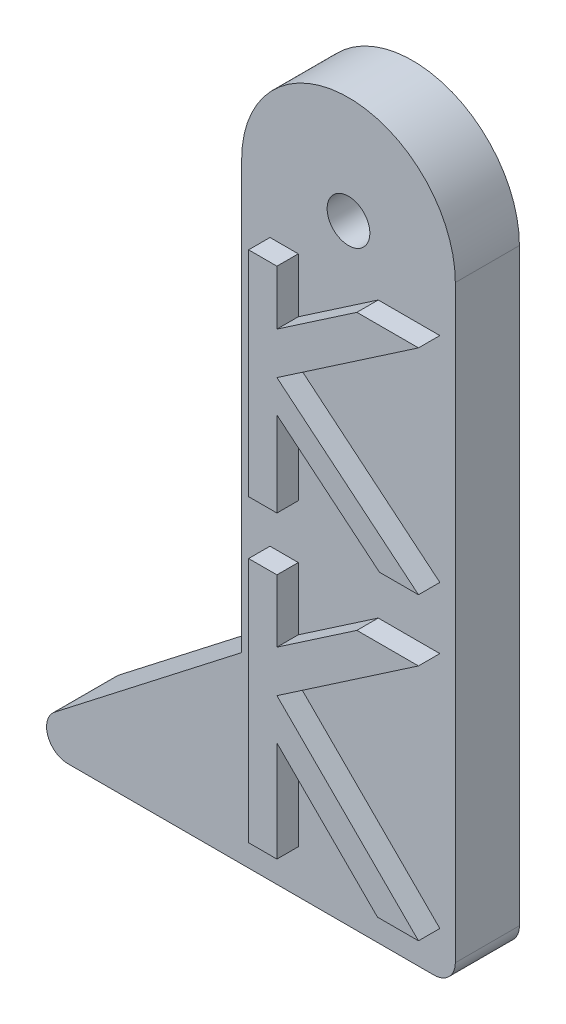
SolidWorks part; units mm, degrees
ref_plane "前视基准面" through (0, 0, 0) normal (0, 0, 1) x (1, 0, 0)
ref_plane "上视基准面" through (0, 0, 0) normal (0, 1, 0) x (1, 0, 0)
ref_plane "右视基准面" through (0, 0, 0) normal (1, 0, 0) x (0, 0, -1)
sketch "草图1" plane through (0, 0, 0) normal (0, 0, 1) x (1, 0, 0)
  line L0 (-5, 0) -> (-5, -20)
  line L1 (-5, -20) -> (5, -20)
  line L2 (5, -20) -> (5, 0)
  arc A0 (5, 0) -> (-5, 0) centre (0, 0) ccw
  circle A1 centre (0, 0) radius 1
  dimension "D1" = 10
  dimension "D2" = 2
extrude "凸台-拉伸1" add sketch "草图1" along normal blind 3
sketch "草图2" plane through (0, 0, 3) normal (0, 0, 1) x (1, 0, 0)
  line L0 (-5, -20) -> (5, -20)
  line L1 (5, -20) -> (5, -28.5715)
  line L2 (-5, -20) -> (-16.0533, -28.5715)
  line L3 (-16.0533, -28.5715) -> (5, -28.5715)
extrude "凸台-拉伸2" add sketch "草图2" against normal up to surface (3 mm away) up to face at (0, -8.75, 0)
fillet "圆角2" radius 1 1 edges at (-16.0533, -28.5715, 1.5)
fillet "圆角3" radius 1 1 edges at (5, -28.5715, 1.5)
sketch "草图3" plane through (0, 0, 3) normal (0, 0, 1) x (1, 0, 0)
  line L0 (-3.675, -2.5104) -> (-3.675, -12.5168)
  line L1 (-3.675, -12.5168) -> (-2.3499, -12.5168)
  line L2 (-2.3499, -12.5168) -> (-2.3499, -8.5417)
  line L3 (-2.3499, -8.5417) -> (2.4477, -12.5168)
  line L4 (2.4477, -12.5168) -> (4.2753, -12.5168)
  line L5 (4.2753, -12.5168) -> (-2.3499, -7.0273)
  line L6 (-2.3499, -7.0273) -> (4.2753, -2.5104)
  line L7 (4.2753, -2.5104) -> (1.3927, -2.5104)
  line L8 (1.3927, -2.5104) -> (-2.3499, -5.062)
  line L9 (-2.3499, -5.062) -> (-2.3499, -2.5104)
  line L10 (-2.3499, -2.5104) -> (-3.675, -2.5104)
  line L11 (-3.675, -15.0235) -> (-3.675, -26.5441)
  line L12 (-3.675, -26.5441) -> (-2.3499, -26.5441)
  line L13 (-2.3499, -26.5441) -> (-2.3499, -21.8379)
  line L14 (-2.3499, -21.8379) -> (2.3563, -26.5441)
  line L15 (2.3563, -26.5441) -> (4.2753, -26.5441)
  line L16 (4.2753, -26.5441) -> (-2.3499, -19.9188)
  line L17 (-2.3499, -19.9188) -> (4.2753, -15.4019)
  line L18 (4.2753, -15.4019) -> (1.3927, -15.4019)
  line L19 (1.3927, -15.4019) -> (-2.3499, -17.9535)
  line L20 (-2.3499, -17.9535) -> (-2.3499, -15.0235)
  line L21 (-2.3499, -15.0235) -> (-3.675, -15.0235)
extrude "凸台-拉伸3" add sketch "草图3" along normal blind 1
